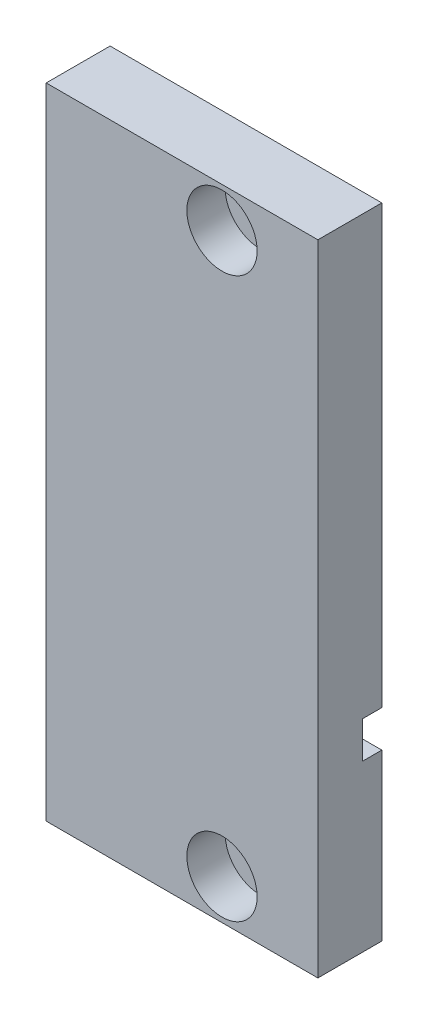
SolidWorks part; units mm, degrees
ref_plane "Plan de face" through (0, 0, 0) normal (0, 0, 1) x (1, 0, 0)
ref_plane "Plan de dessus" through (0, 0, 0) normal (0, 1, 0) x (1, 0, 0)
ref_plane "Plan de droite" through (0, 0, 0) normal (1, 0, 0) x (0, 0, -1)
sketch "Esquisse1" plane through (0, 0, 0) normal (0, 0, 1) x (1, 0, 0)
  line L1 (-7, -17.5) -> (10, -17.5)
  line L2 (-7, -17.5) -> (-7, 22.5)
  line L3 (-7, 22.5) -> (10, 22.5)
  line L4 (10, -17.5) -> (10, 22.5)
extrude "Boss.-Extru.1" add sketch "Esquisse1" along normal blind 4
sketch "Esquisse4" plane through (0, 0, 4) normal (0, 0, 1) x (1, 0, 0)
  point P0 (4, -15)
  point P3 (4, 20)
hole_wizard "Chambrage pour vis à six pans creux M21" positions "Esquisse4" profile "Esquisse3" counterbore size "M2" standard "ISO" end condition up to next
sketch "Esquisse3" plane through (4, -15, 4) normal (1, 0, 0) x (0, -1, 0)
  line L0 (0, 0) -> (0, 4)
  line L1 (0, 4) -> (1.2, 4)
  line L3 (1.2, 4) -> (1.2, 2.4)
  line L4 (1.2, 2.4) -> (2.2, 2.4)
  line L5 (2.2, 2.4) -> (2.2, 0)
  line L7 (2.2, 0) -> (0, 0)
  line L11 (0, -6.35) -> (0, 107.95) construction
  dimension "Diamètre du perçage jusqu'au prochain" = 2.4
  dimension "Profondeur du perçage jusqu'au prochain" = 4
  dimension "Diamètre du chambrage" = 4.4
  dimension "Profondeur du chambrage" = 2.4
sketch "Esquisse7" plane through (0, 0, 0) normal (0, 0, -1) x (-1, 0, 0)
  line L5 (-10, -17.5) -> (-10, 22.5) construction
  line L10 (2, 17.5) -> (2, -4.85) construction
  line L13 (2, -4.85) -> (-10, -4.85)
  line L14 (2, -4.85) -> (2, -7.15)
  line L15 (2, -7.15) -> (-10, -7.15)
  line L16 (-10, -4.85) -> (-10, -7.15)
  line L17 (-0.66, -6) -> (0.66, -6) construction
  line L18 (-10, 17.5) -> (2, 17.5) construction
  line L19 (-2.85, 17.5) -> (-5.15, 17.5)
  line L20 (-2.85, 17.5) -> (-2.85, 2.5)
  line L21 (-2.85, 2.5) -> (-5.15, 2.5)
  line L22 (-5.15, 17.5) -> (-5.15, 2.5)
  line L23 (-4, 0.66) -> (-4, -0.66) construction
  point P14 (2, -6)
  point P17 (-4, 17.5)
  dimension "D1" = 2.3
  dimension "D2" = 2.3
  dimension "D3" = 15
extrude "Enlèv. mat.-Extru.1" cut sketch "Esquisse7" against normal blind 1.2
